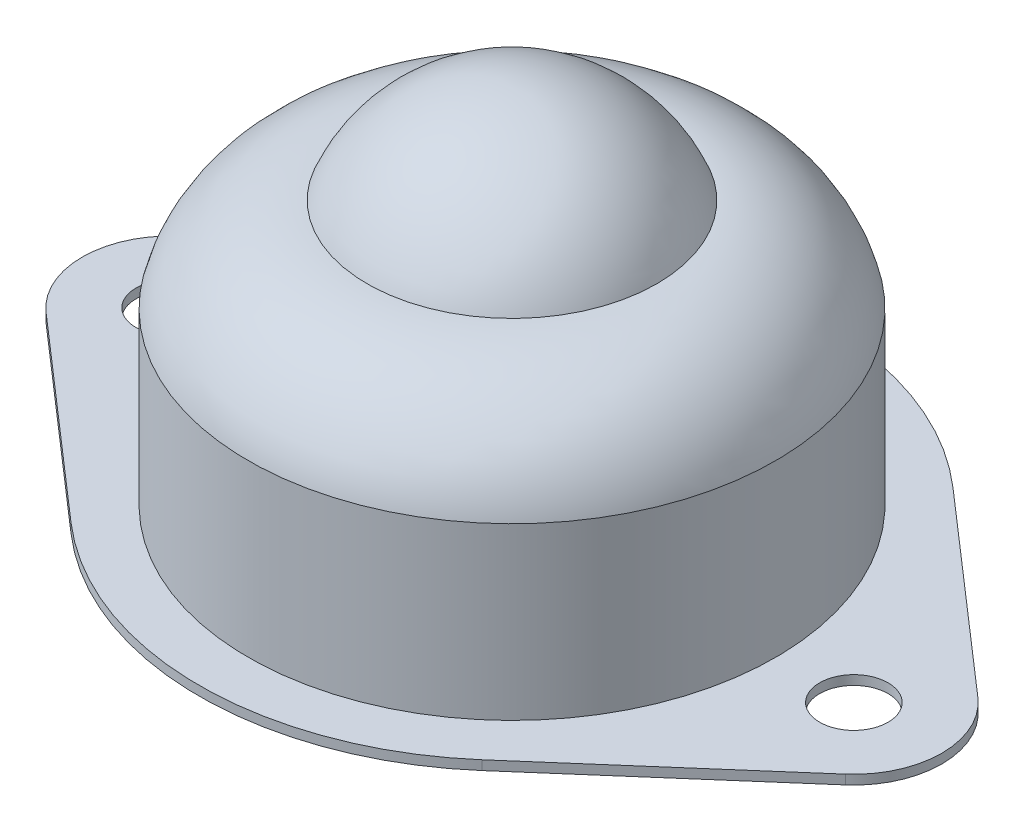
SolidWorks part; units mm, degrees
ref_plane "Front Plane" through (0, 0, 0) normal (0, 0, 1) x (1, 0, 0)
ref_plane "Top Plane" through (0, 0, 0) normal (0, 1, 0) x (1, 0, 0)
ref_plane "Right Plane" through (0, 0, 0) normal (1, 0, 0) x (0, 0, -1)
sketch "Sketch1" plane through (0, 0, 0) normal (0, 1, 0) x (1, 0, 0)
  line L0 (-27.7812, 0) -> (27.7812, 0) construction
  line L1 (0, 0) -> (-34.925, 0) construction
  line L2 (0, 0) -> (34.925, 0) construction
  line L3 (-16.6914, 19.1457) -> (-32.4757, 5.3847)
  line L4 (16.6914, 19.1457) -> (32.4757, 5.3847)
  line L5 (-16.6914, -19.1457) -> (-32.4757, -5.3847)
  line L6 (16.6914, -19.1457) -> (32.4757, -5.3847)
  circle A0 centre (-27.7812, 0) radius 2.7781
  circle A1 centre (27.7812, 0) radius 2.7781
  circle A2 centre (0, 0) radius 25.4 construction
  circle A3 centre (-27.7812, 0) radius 7.1437 construction
  circle A4 centre (27.7812, 0) radius 7.1437 construction
  arc A5 (-16.6914, 19.1457) -> (16.6914, 19.1457) centre (0, 0) cw
  arc A6 (-16.6914, -19.1457) -> (16.6914, -19.1457) centre (0, 0) ccw
  arc A7 (-32.4757, -5.3847) -> (-32.4757, 5.3847) centre (-27.7812, 0) cw
  arc A8 (32.4757, 5.3847) -> (32.4757, -5.3847) centre (27.7812, 0) cw
  dimension "D2" = 50.8
  dimension "D3" = 34.925
  dimension "D4" = 5.5562
  dimension "D1" = 55.5625
extrude "Boss-Extrude1" add sketch "Sketch1" along normal blind 0.762
sketch "Sketch2" plane through (0, 0, 0) normal (0, 0, 1) x (1, 0, 0)
  line L0 (0, 0) -> (0, 17.4625) construction
  line L1 (0, 0) -> (21.4312, 0) construction
  line L2 (-16.6914, 0) -> (16.6914, 0) construction
  line L3 (21.4312, 0) -> (21.4312, 22.225) construction
  line L4 (21.4312, 22.225) -> (11.7732, 22.225) construction
  line L5 (21.4312, 14.605) -> (21.4312, 0)
  line L6 (21.4312, 22.225) -> (21.4312, 14.605) construction
  line L7 (21.4312, 0) -> (0, 0)
  line L8 (0, 0) -> (0, 30.1625)
  circle A0 centre (0, 17.4625) radius 12.7 construction
  arc A1 (11.7732, 22.225) -> (21.4312, 14.605) centre (11.7732, 12.2944) cw
  arc A2 (0, 30.1625) -> (11.7732, 22.225) centre (0, 17.4625) cw
  dimension "D1" = 25.4
  dimension "D2" = 17.4625
  dimension "D3" = 21.4312
  dimension "D4" = 22.225
  dimension "D5" = 7.62
revolve "Revolve1" add sketch "Sketch2" angle 360 about L8
